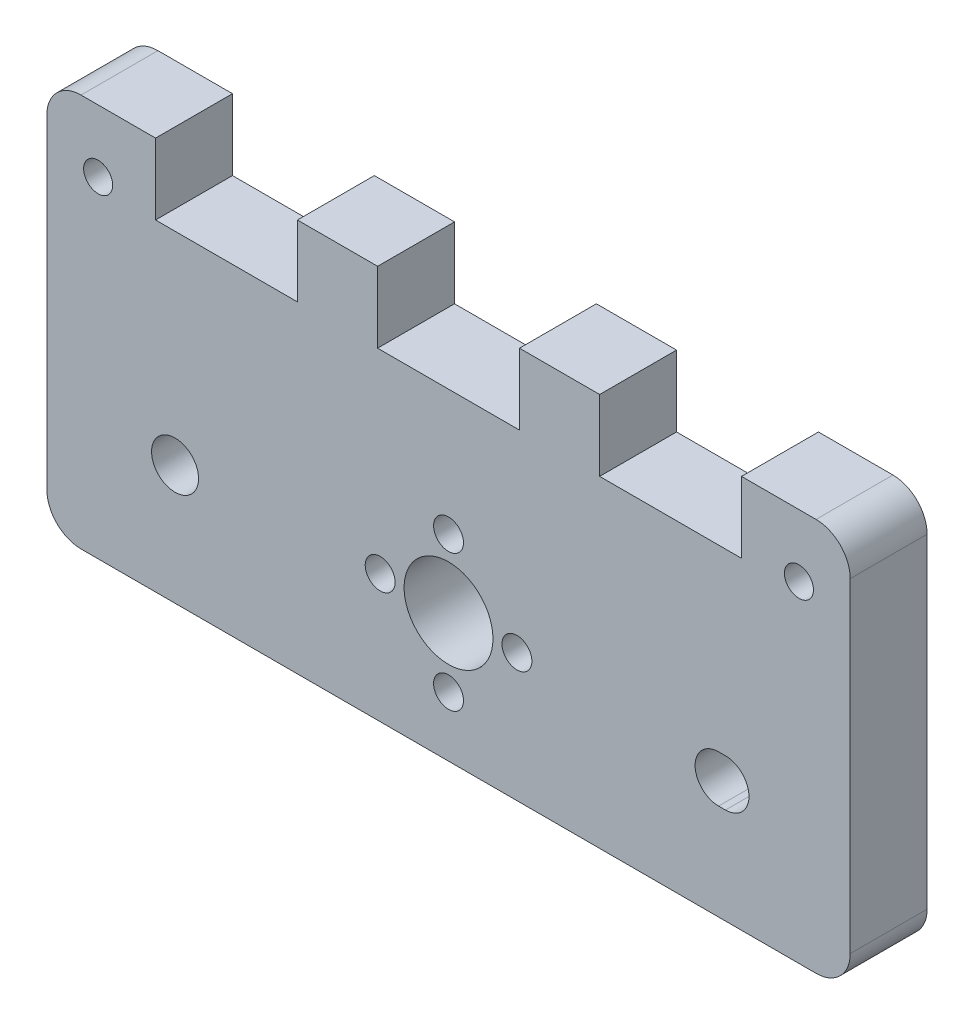
SolidWorks part; units mm, degrees
ref_plane "Front Plane" through (0, 0, 0) normal (0, 0, 1) x (1, 0, 0)
ref_plane "Top Plane" through (0, 0, 0) normal (0, 1, 0) x (1, 0, 0)
ref_plane "Right Plane" through (0, 0, 0) normal (1, 0, 0) x (0, 0, -1)
sketch "S01 - Common slider blank" plane through (0, 0, 0) normal (0, 0, 1) x (1, 0, 0)
  line L0 (-43, -97) -> (43, -97)
  line L1 (47, -93) -> (47, -55)
  line L2 (43, -51) -> (-43, -51)
  line L3 (-47, -55) -> (-47, -93)
  arc A0 (43, -97) -> (47, -93) centre (43, -93) ccw
  arc A1 (47, -55) -> (43, -51) centre (43, -55) ccw
  arc A2 (-43, -51) -> (-47, -55) centre (-43, -55) ccw
  arc A3 (-47, -93) -> (-43, -97) centre (-43, -93) ccw
  dimension "D1" = 4
  dimension "D2" = 47
  dimension "D3" = 47
  dimension "D4" = 51
  dimension "D5" = 97
extrude "01 - Common slider blank" add sketch "S01 - Common slider blank" along normal blind 9
sketch "S02 - Round locating guide and relieved companion" plane through (0, 0, 0) normal (0, 0, 1) x (1, 0, 0)
  line L0 (31.6, -80.25) -> (32.4, -80.25)
  line L1 (32.4, -85.75) -> (31.6, -85.75)
  circle A0 centre (-32, -83) radius 2.75
  arc A1 (32.4, -80.25) -> (32.4, -85.75) centre (32.4, -83) cw
  arc A2 (31.6, -85.75) -> (31.6, -80.25) centre (31.6, -83) cw
  dimension "D1" = 5.5
  dimension "D2" = 31.6
  dimension "D3" = 32.4
  dimension "D4" = 32
  dimension "D5" = 83
extrude "02 - Round locating guide and relieved companion" cut sketch "S02 - Round locating guide and relieved companion" along normal blind 10 from offset 0.5 offset against normal yes
sketch "S03 - Three drop-in spring seats" plane through (0, 0, 0) normal (0, 0, 1) x (1, 0, 0)
  line L0 (-34.2808, -59.3) -> (-17.6808, -59.3)
  line L1 (-17.6808, -59.3) -> (-17.6808, -50)
  line L2 (-17.6808, -50) -> (-34.2808, -50)
  line L3 (-34.2808, -50) -> (-34.2808, -59.3)
  line L4 (17.6808, -59.3) -> (34.2808, -59.3)
  line L5 (34.2808, -59.3) -> (34.2808, -50)
  line L6 (34.2808, -50) -> (17.6808, -50)
  line L7 (17.6808, -50) -> (17.6808, -59.3)
  line L8 (-8.3, -59.3) -> (8.3, -59.3)
  line L9 (8.3, -59.3) -> (8.3, -50)
  line L10 (8.3, -50) -> (-8.3, -50)
  line L11 (-8.3, -50) -> (-8.3, -59.3)
  dimension "D1" = 8.3
  dimension "D2" = 17.6808
  dimension "D3" = 34.2808
  dimension "D4" = 8.3
  dimension "D5" = 17.6808
  dimension "D6" = 34.2808
  dimension "D7" = 50
  dimension "D8" = 59.3
extrude "03 - Three drop-in spring seats" cut sketch "S03 - Three drop-in spring seats" along normal blind 10 from offset 0.5 offset against normal yes
sketch "S04 - Keeper screw holes" plane through (0, 0, 0) normal (0, 0, 1) x (1, 0, 0)
  circle A0 centre (-41, -58.3) radius 1.7
  circle A1 centre (41, -58.3) radius 1.7
  dimension "D1" = 3.4
  dimension "D2" = 3.4
  dimension "D3" = 41
  dimension "D4" = 41
  dimension "D5" = 58.3
extrude "04 - Keeper screw holes" cut sketch "S04 - Keeper screw holes" along normal blind 10 from offset 0.5 offset against normal yes
sketch "S07 - Clearance tunnel for rotating spindle retainer" plane through (0, 0, 0) normal (0, 0, 1) x (1, 0, 0)
  circle A0 centre (0, -82) radius 5.2
  dimension "D1" = 10.4
  dimension "D2" = 82
extrude "07 - Clearance tunnel for rotating spindle retainer" cut sketch "S07 - Clearance tunnel for rotating spindle retainer" along normal through all from offset 0.15 offset against normal yes
sketch "Sketch1" plane through (0, 0, 9) normal (0, 0, 1) x (1, 0, 0)
  circle A1 centre (8, -82) radius 1.75
  circle A4 centre (0, -74) radius 1.75
  circle A5 centre (0, -90) radius 1.75
  circle A6 centre (-8, -82) radius 1.7503
extrude "Cut-Extrude1" cut sketch "Sketch1" against normal blind 10
